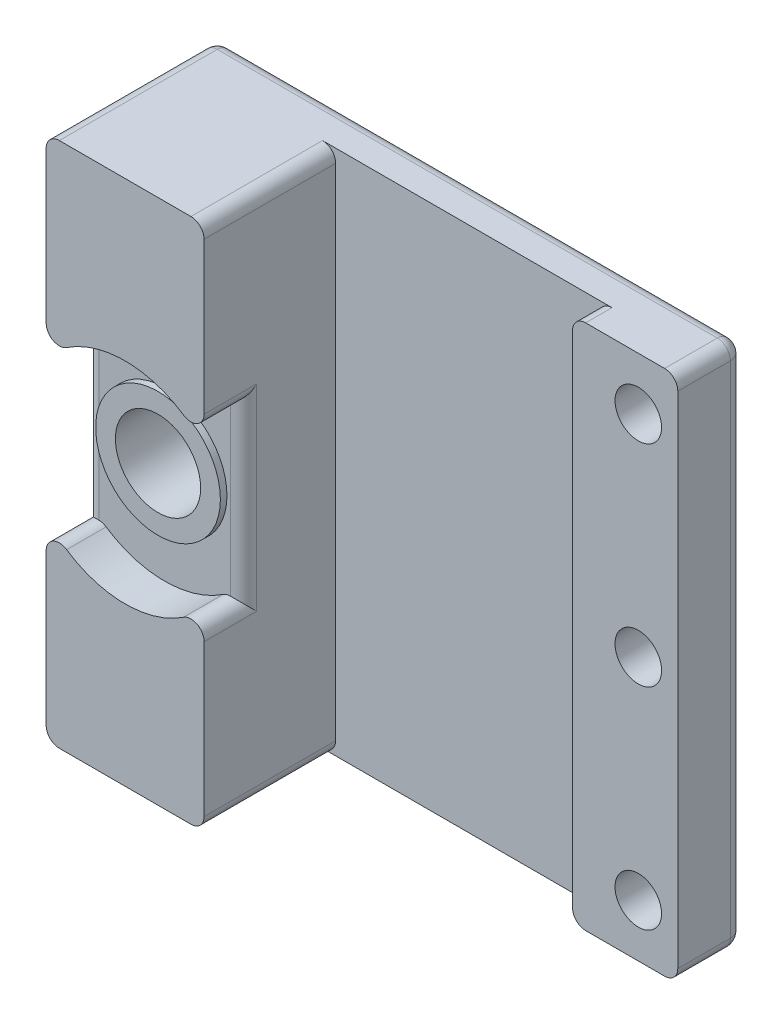
SolidWorks part; units mm, degrees
material "ABS"
ref_plane "Front" through (0, 0, 0) normal (0, 0, 1) x (1, 0, 0)
ref_plane "Top" through (0, 0, 0) normal (0, 1, 0) x (1, 0, 0)
ref_plane "Right" through (0, 0, 0) normal (1, 0, 0) x (0, 0, -1)
sketch "Sketch2" plane through (0, 0, 0) normal (0, 0, 1) x (1, 0, 0)
  line L0 (0, 31.75) -> (63.5, 31.75) construction
  line L1 (0, 0) -> (63.5, 0)
  line L2 (0, 0) -> (0, 63.5)
  line L3 (0, 63.5) -> (63.5, 63.5)
  line L4 (63.5, 0) -> (63.5, 63.5)
  line L5 (20.6375, 63.5) -> (20.6375, 0) construction
  circle A0 centre (9.525, 31.75) radius 11.1125 construction
  circle A1 centre (9.525, 31.75) radius 5.1435
  dimension "D2" = 22.225
  dimension "D3" = 10.287
  dimension "D1" = 42.8625
  dimension "D4" = 9.525
  dimension "D5" = 63.5
extrude "Boss-Extrude1" add sketch "Sketch2" along normal blind 20.6375
sketch "Sketch3" plane through (0, 0, 0) normal (0, -1, 0) x (1, 0, 0)
  line L0 (0, 20.6375) -> (63.5, 20.6375) construction
  line L1 (19.05, 20.6375) -> (50.8, 20.6375)
  line L2 (19.05, 20.6375) -> (19.05, 4.7625)
  line L3 (19.05, 4.7625) -> (50.8, 4.7625)
  line L4 (50.8, 20.6375) -> (50.8, 4.7625)
  line L5 (63.5, 20.6375) -> (63.5, 0) construction
  dimension "D1" = 15.875
  dimension "D2" = 12.7
  dimension "D3" = 31.75
extrude "Cut-Extrude1" cut sketch "Sketch3" against normal through all
sketch "Sketch4" plane through (0, 0, 0) normal (0, -1, 0) x (1, 0, 0)
  line L0 (63.5, 20.6375) -> (63.5, 0) construction
  line L1 (50.8, 20.6375) -> (63.5, 20.6375)
  line L2 (50.8, 20.6375) -> (50.8, 7.9375)
  line L3 (50.8, 7.9375) -> (63.5, 7.9375)
  line L4 (63.5, 20.6375) -> (63.5, 7.9375)
  dimension "D1" = 12.7
extrude "Cut-Extrude2" cut sketch "Sketch4" against normal through all
sketch "Sketch5" plane through (0, 0, 20.6375) normal (0, 0, 1) x (1, 0, 0)
  circle A0 centre (9.525, 31.75) radius 12.7
  dimension "D1" = 25.4
extrude "Cut-Extrude3" cut sketch "Sketch5" against normal blind 3.9688
sketch "Sketch6" plane through (0, 0, 16.6687) normal (0, 0, 1) x (1, 0, 0)
  circle A0 centre (9.525, 31.75) radius 12.7
  circle A1 centre (9.525, 31.75) radius 7.5248
  circle A2 centre (9.525, 31.75) radius 5.1435 construction
  dimension "D1" = 2.3813
extrude "Cut-Extrude4" cut sketch "Sketch6" against normal blind 0.7937
fillet "Fillet1" radius 1.5875 16 edges at (19.05, 0, 12.7) (50.8, 0, 6.35) (63.5, 0, 3.9688) (63.5, 63.5, 3.9688) (50.8, 63.5, 6.35) (19.05, 63.5, 12.7) (0, 63.5, 10.3187) (31.75, 63.5, 0) (63.5, 31.75, 0) (0, 31.75, 0) (31.75, 0, 0) (0, 0, 10.3187) (0, 31.75, 15.875) (0, 40.1503, 18.2563) (19.05, 40.1503, 18.2563) (19.05, 31.75, 15.875)
hole_wizard "#10 Clearance Hole1" positions "Sketch7" profile "Sketch8" hole size "#10" standard "ANSI Inch"
sketch "Sketch7" plane through (0, 0, 20.6375) normal (0, 0, 1) x (1, 0, 0)
  line L0 (58.7375, 63.5) -> (58.7375, 0) construction
  line L1 (52.3875, 63.5) -> (61.9125, 63.5) construction
  line L2 (52.3875, 0) -> (61.9125, 0) construction
  line L4 (50.8, 61.9125) -> (50.8, 1.5875) construction
  point P10 (58.7375, 31.75)
  point P12 (58.7375, 57.15)
  point P14 (58.7375, 6.35)
  dimension "D1" = 7.9375
  dimension "D2" = 25.4
  dimension "D3" = 25.4
sketch "Sketch8" plane through (58.7375, 6.35, 20.6375) normal (1, 0, 0) x (0, -1, 0)
  line L0 (0, 0) -> (0, 27.0864)
  line L1 (0, 27.0864) -> (2.8067, 25.4)
  line L2 (2.8067, 25.4) -> (2.8067, 0)
  line L5 (2.8067, 0) -> (0, 0)
  line L10 (0, 27.0864) -> (-2.8067, 25.4) construction
  line L11 (0, -6.35) -> (0, 107.95) construction
  dimension "Hole Dia." = 5.6134
  dimension "Hole Depth" = 25.4
  dimension "Drill Angle" = 118
